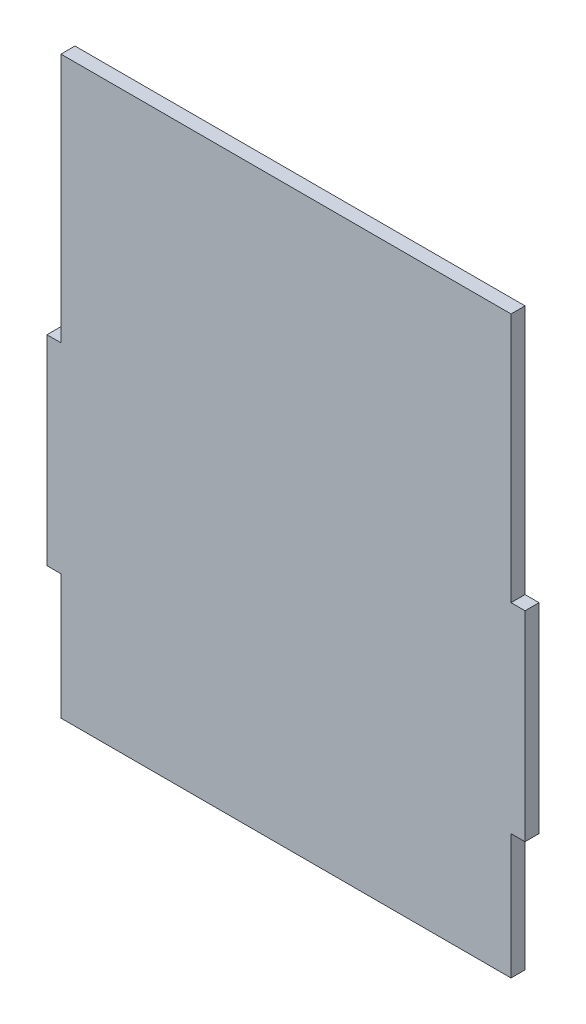
SolidWorks part; units mm, degrees
material "Фанера"
ref_plane "Front Plane" through (0, 0, 0) normal (0, 0, 1) x (1, 0, 0)
ref_plane "Top Plane" through (0, 0, 0) normal (0, 1, 0) x (1, 0, 0)
ref_plane "Right Plane" through (0, 0, 0) normal (1, 0, 0) x (0, 0, -1)
sketch "Эскиз1" plane through (0, 0, 0) normal (0, 0, 1) x (1, 0, 0)
  line L0 (-45, 7.5) -> (-45, 57.5)
  line L1 (-45, -57.5) -> (45, -57.5)
  line L2 (-45, -57.5) -> (-45, -32.5)
  line L3 (-45, 57.5) -> (45, 57.5)
  line L4 (45, -57.5) -> (45, -32.5)
  line L5 (-45, -57.5) -> (45, 57.5) construction
  line L6 (-45, 57.5) -> (45, -57.5) construction
  line L7 (-45, -32.5) -> (-47.8, -32.5)
  line L9 (-45, 7.5) -> (-47.8, 7.5)
  line L10 (-47.8, -32.5) -> (-47.8, 7.5)
  line L11 (-45, -12.5) -> (-47.8, 7.5) construction
  line L12 (-45, -12.5) -> (-47.8, -32.5) construction
  line L13 (0, 49.6792) -> (0, -68.975) construction
  line L14 (45, -32.5) -> (47.8, -32.5)
  line L15 (47.8, -32.5) -> (47.8, 7.5)
  line L16 (45, 7.5) -> (47.8, 7.5)
  line L17 (45, 7.5) -> (45, 57.5)
  point P0 (0, 0)
  point P5 (-45, -12.5)
  point P18 (0, 0)
  point P19 (-45, -6.583)
  dimension "D1" = 115
  dimension "D2" = 90
  dimension "D3" = 40
  dimension "D4" = 2.8
  dimension "D5" = 20
  dimension "D6" = 45
extrude "Бобышка-Вытянуть1" add sketch "Эскиз1" along normal mid plane 2.8
